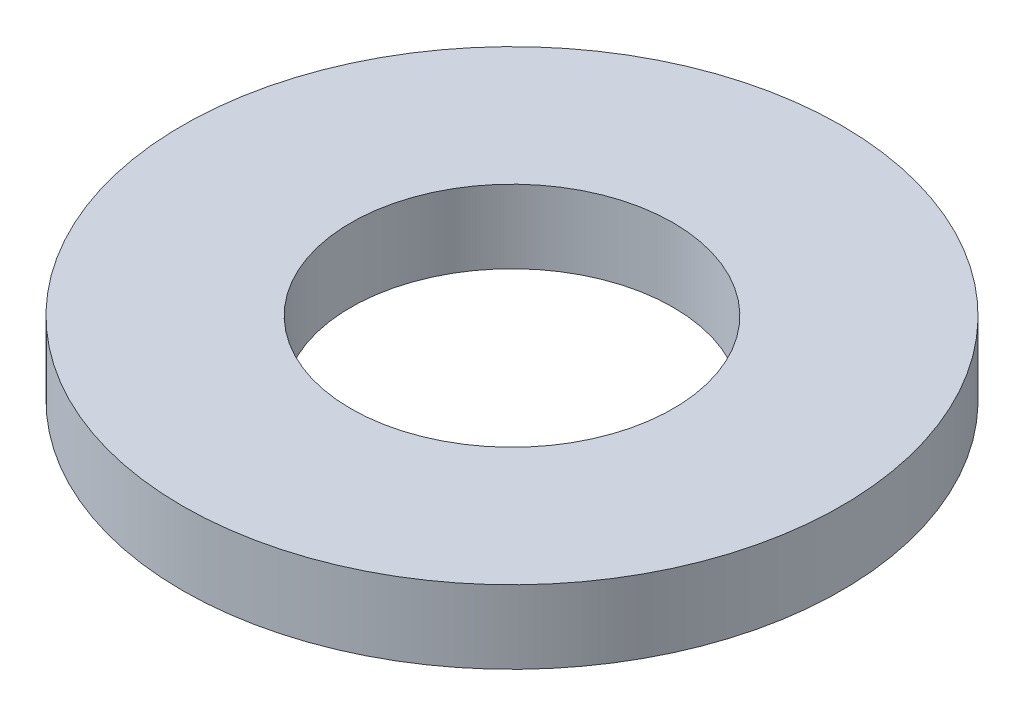
SolidWorks part; units mm, degrees
ref_plane "前视基准面" through (0, 0, 0) normal (0, 0, 1) x (1, 0, 0)
ref_plane "上视基准面" through (0, 0, 0) normal (0, 1, 0) x (1, 0, 0)
ref_plane "右视基准面" through (0, 0, 0) normal (1, 0, 0) x (0, 0, -1)
other "Configuration Table"
sketch "草图1" plane through (0, 0, 0) normal (0, 1, 0) x (1, 0, 0)
  circle A0 centre (0, 0) radius 4.5
  circle A1 centre (0, 0) radius 2.2
  dimension "D1" = 9
  dimension "D2" = 4.4
extrude "凸台-拉伸1" add sketch "草图1" along normal blind 1
